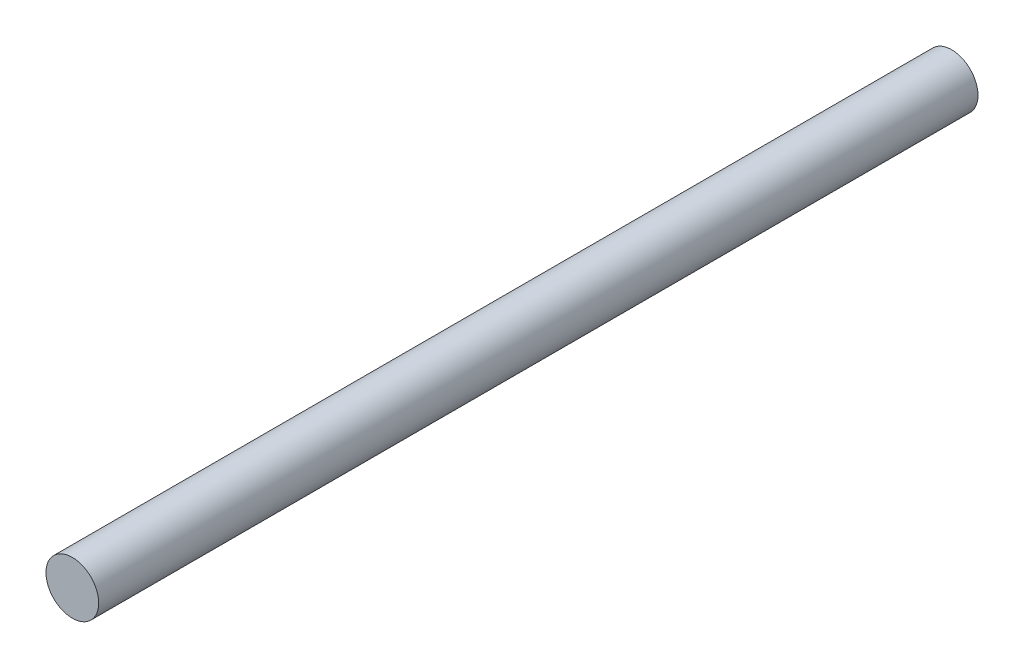
SolidWorks part; units mm, degrees
ref_plane "Front" through (0, 0, 0) normal (0, 0, 1) x (1, 0, 0)
ref_plane "Top" through (0, 0, 0) normal (0, 1, 0) x (1, 0, 0)
ref_plane "Right" through (0, 0, 0) normal (1, 0, 0) x (0, 0, -1)
sketch "Skizze1" plane through (0, 0, 0) normal (0, 0, 1) x (1, 0, 0)
  circle A0 centre (0, 0) radius 6
  dimension "D1" = 12
extrude "Aufsatz-Linear austragen1" add sketch "Skizze1" along normal blind 200
